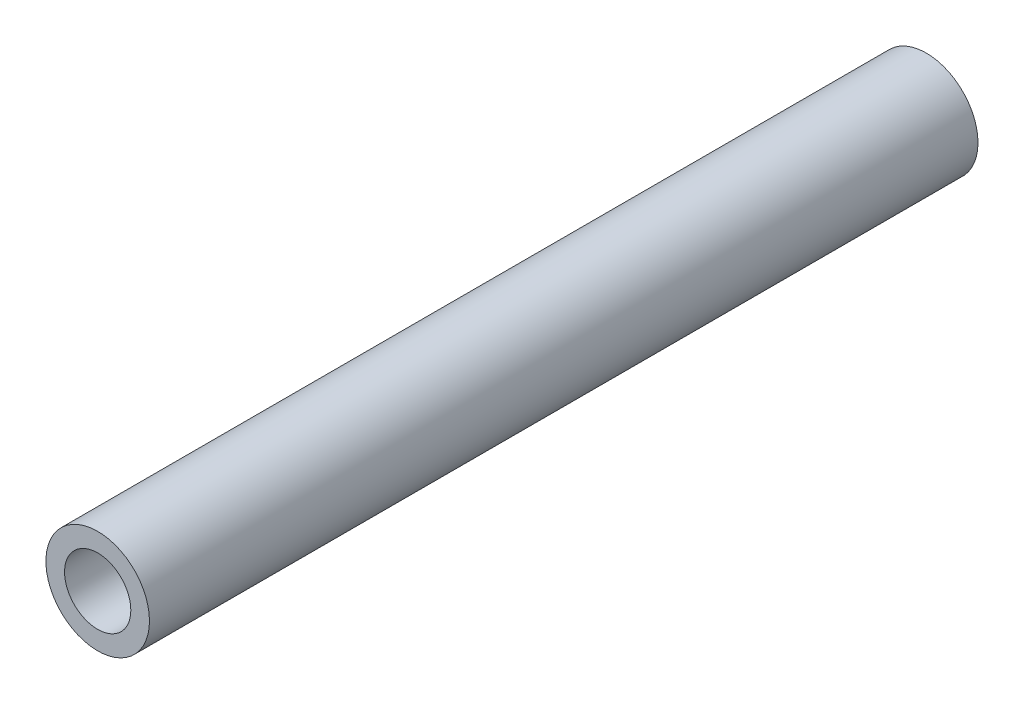
SolidWorks part; units mm, degrees
ref_plane "Front" through (0, 0, 0) normal (0, 0, 1) x (1, 0, 0)
ref_plane "Top" through (0, 0, 0) normal (0, 1, 0) x (1, 0, 0)
ref_plane "Right" through (0, 0, 0) normal (1, 0, 0) x (0, 0, -1)
sketch "草图1" plane through (0, 0, 0) normal (0, 0, 1) x (1, 0, 0)
  circle A0 centre (0, 0) radius 2.5
  circle A1 centre (0, 0) radius 1.6
  dimension "D1" = 3.2
  dimension "D2" = 5
extrude "凸台-拉伸1" add sketch "草图1" along normal blind 40
